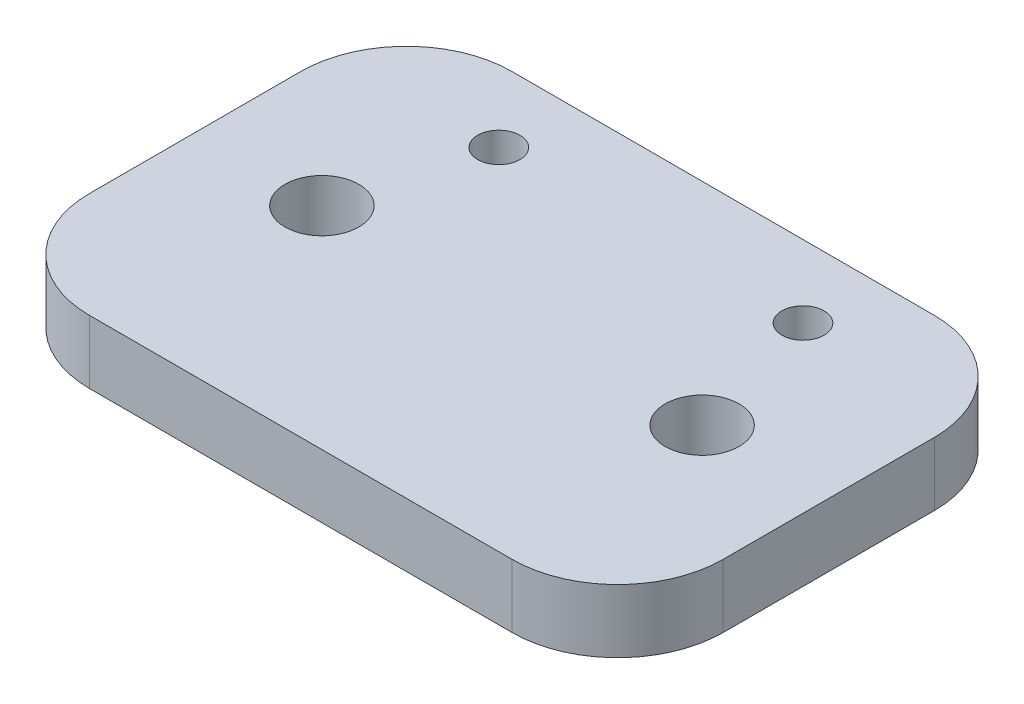
SolidWorks part; units mm, degrees
ref_plane "前视基准面" through (0, 0, 0) normal (0, 0, 1) x (1, 0, 0)
ref_plane "上视基准面" through (0, 0, 0) normal (0, 1, 0) x (1, 0, 0)
ref_plane "右视基准面" through (0, 0, 0) normal (1, 0, 0) x (0, 0, -1)
other "Configuration Table"
sketch "草图1" plane through (0, 0, 0) normal (0, 1, 0) x (1, 0, 0)
  line L1 (-10, -10) -> (10, -10)
  line L2 (-15, -5) -> (-15, 5)
  line L3 (-10, 10) -> (10, 10)
  line L4 (15, -5) -> (15, 5)
  line L5 (-15, -10) -> (15, 10) construction
  line L6 (-15, 10) -> (15, -10) construction
  arc A0 (10, -10) -> (15, -5) centre (10, -5) ccw
  arc A1 (-10, -10) -> (-15, -5) centre (-10, -5) cw
  arc A2 (10, 10) -> (15, 5) centre (10, 5) cw
  arc A3 (-15, 5) -> (-10, 10) centre (-10, 5) cw
  circle A4 centre (-9, 0) radius 1.75
  circle A5 centre (9, 0) radius 1.75
  circle A6 centre (7.2, 6.575) radius 1
  circle A7 centre (-7.2, 6.575) radius 1
  point P0 (0, 0)
  point P22 (15, 0)
  dimension "D3" = 5
  dimension "D4" = 6
  dimension "D5" = 6
  dimension "D6" = 3.5
  dimension "D7" = 3.5
  dimension "D1" = 30
  dimension "D2" = 20
extrude "凸台-拉伸1" add sketch "草图1" along normal blind 3
